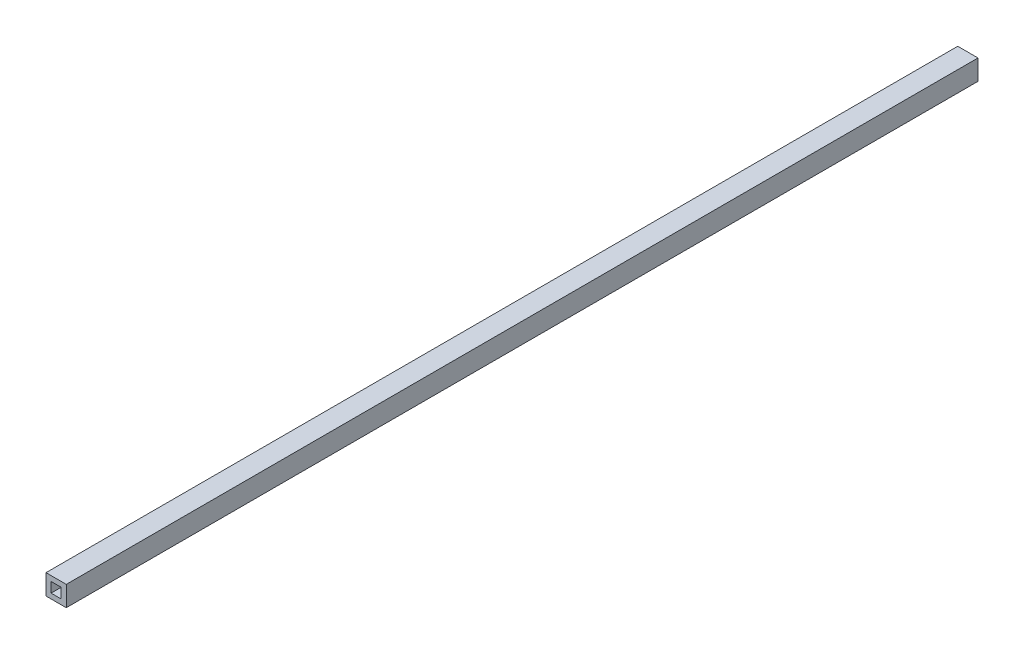
SolidWorks part; units mm, degrees
material "6063-O"
ref_plane "Front Plane" through (0, 0, 0) normal (0, 0, 1) x (1, 0, 0)
ref_plane "Top Plane" through (0, 0, 0) normal (0, 1, 0) x (1, 0, 0)
ref_plane "Right Plane" through (0, 0, 0) normal (1, 0, 0) x (0, 0, -1)
sketch "Sketch1" plane through (0, 0, 0) normal (0, 0, 1) x (1, 0, 0)
  line L1 (-10, -10) -> (10, -10)
  line L2 (-10, -10) -> (-10, 10)
  line L3 (-10, 10) -> (10, 10)
  line L4 (10, -10) -> (10, 10)
  line L5 (-10, -10) -> (10, 10) construction
  line L6 (-10, 10) -> (10, -10) construction
  point P0 (0, 0)
  dimension "D1" = 20
extrude "Extrude-Thin1" add sketch "Sketch1" along normal blind 900 thin thin type one direction reverse wall 5
